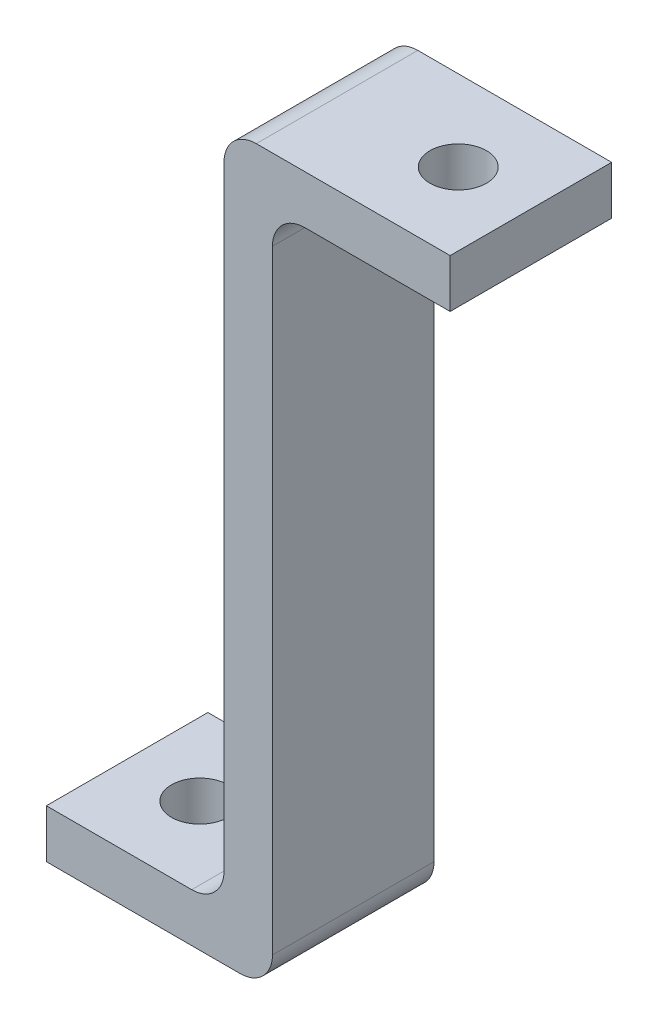
SolidWorks part; units mm, degrees
ref_plane "Front Plane" through (0, 0, 0) normal (0, 0, 1) x (1, 0, 0)
ref_plane "Top Plane" through (0, 0, 0) normal (0, 1, 0) x (1, 0, 0)
ref_plane "Right Plane" through (0, 0, 0) normal (1, 0, 0) x (0, 0, -1)
sketch "Sketch1" plane through (0, 0, 0) normal (0, 0, 1) x (1, 0, 0)
  line L0 (0, 0) -> (14, 0)
  line L1 (14, 0) -> (14, 42)
  line L2 (14, 42) -> (25, 42)
  line L3 (25, 42) -> (25, 45)
  line L4 (25, 45) -> (11, 45)
  line L5 (11, 45) -> (11, 3)
  line L6 (11, 3) -> (0, 3)
  line L7 (0, 3) -> (0, 0)
  dimension "D1" = 3
  dimension "D2" = 3
  dimension "D3" = 11
  dimension "D4" = 3
  dimension "D5" = 11
  dimension "D6" = 42
extrude "Boss-Extrude1" add sketch "Sketch1" against normal blind 10
fillet "Fillet1" radius 2 4 edges at (14, 0, -5) (11, 45, -5) (11, 3, -5) (14, 42, -5)
hole_wizard "Ø3.0mm Dowel Hole1" positions "3DSketch1" profile "Sketch2" hole size "Ø3.0" standard "ANSI Metric" end condition through all
sketch3d "3DSketch1"
  line L0 (0, 0, -5) -> (12, 0, -5) construction
  line L1 (0, 0, -10) -> (0, 0, 0) construction
  line L2 (12, 0, -10) -> (12, 0, 0) construction
  line L4 (4.5, 0, -5) -> (4.5, 0, -10) construction
  line L6 (0, 0, -10) -> (12, 0, -10) construction
  point P0 (4.5, 0, -5)
  point P14 (4.229, 0, -10)
  point P17 (4.4364, 0, -10)
  point P18 (4.5, 0, -5)
  dimension "D1" = 4.5
sketch "Sketch2" plane through (4.5, 0, -5) normal (1, 0, 0) x (0, 0, -1)
  line L0 (0, 0) -> (0, 45)
  line L1 (0, 45) -> (1.75, 45)
  line L2 (1.75, 45) -> (1.75, 0)
  line L5 (1.75, 0) -> (0, 0)
  line L11 (0, -6.35) -> (0, 107.95) construction
  dimension "Thru Hole Dia." = 3.5
  dimension "Thru Hole Depth" = 45
hole_wizard "Ø3.0mm Dowel Hole2" positions "Sketch3" profile "Sketch4" hole size "Ø3.0" standard "ANSI Metric" end condition through all
sketch "Sketch3" plane through (0, 45, 0) normal (0, 1, 0) x (1, 0, 0)
  line L0 (25, 5) -> (13, 5) construction
  line L1 (25, 10) -> (25, 0) construction
  line L2 (13, 10) -> (13, 0) construction
  line L4 (20.5, 5) -> (20.5, 10) construction
  line L5 (25, 10) -> (13, 10) construction
  point P0 (20.5, 5)
  point P17 (20.5, 5)
  dimension "D1" = 4.5
sketch "Sketch4" plane through (20.5, 45, -5) normal (1, 0, 0) x (0, 0, 1)
  line L0 (0, 0) -> (0, 45)
  line L1 (0, 45) -> (1.75, 45)
  line L2 (1.75, 45) -> (1.75, 0)
  line L5 (1.75, 0) -> (0, 0)
  line L11 (0, -6.35) -> (0, 107.95) construction
  dimension "Thru Hole Dia." = 3.5
  dimension "Thru Hole Depth" = 45
